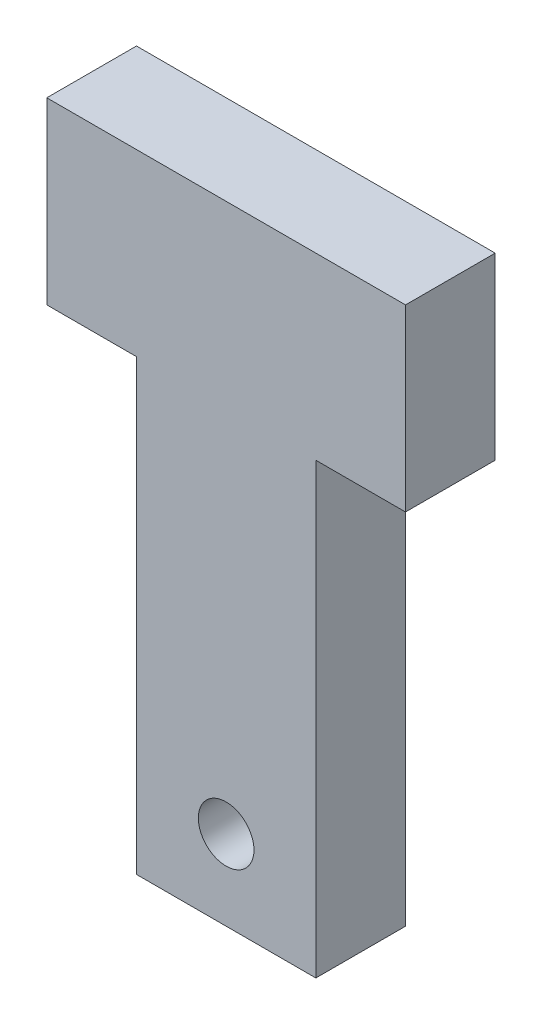
SolidWorks part; units mm, degrees
ref_plane "前基準面" through (0, 0, 0) normal (0, 0, 1) x (1, 0, 0)
ref_plane "上基準面" through (0, 0, 0) normal (0, 1, 0) x (1, 0, 0)
ref_plane "右基準面" through (0, 0, 0) normal (1, 0, 0) x (0, 0, -1)
sketch "草圖1" plane through (0, 0, 0) normal (0, 0, 1) x (1, 0, 0)
  line L0 (-5, -5) -> (-10, -5)
  line L1 (10, 5) -> (-10, 5)
  line L2 (10, 5) -> (10, -5)
  line L3 (10, -5) -> (5, -5)
  line L4 (-10, 5) -> (-10, -5)
  line L5 (0, -4.801) -> (0, 5) construction
  line L6 (10, 0) -> (-10, 0) construction
  line L7 (5, -30) -> (-5, -30)
  line L8 (5, -30) -> (5, -5)
  line L10 (-5, -30) -> (-5, -5)
  line L11 (0, -4.801) -> (0, -30) construction
  line L12 (5, -17.5) -> (-5, -17.5) construction
  circle A0 centre (0, -25.55) radius 1.55
  point P0 (0, 0)
  point P4 (0, -17.5)
  point P14 (0, -24)
  dimension "D5" = 3.1
  dimension "D1" = 10
  dimension "D2" = 20
  dimension "D3" = 10
  dimension "D4" = 25
  dimension "D6" = 19
extrude "填料-伸長1" add sketch "草圖1" along normal blind 5
